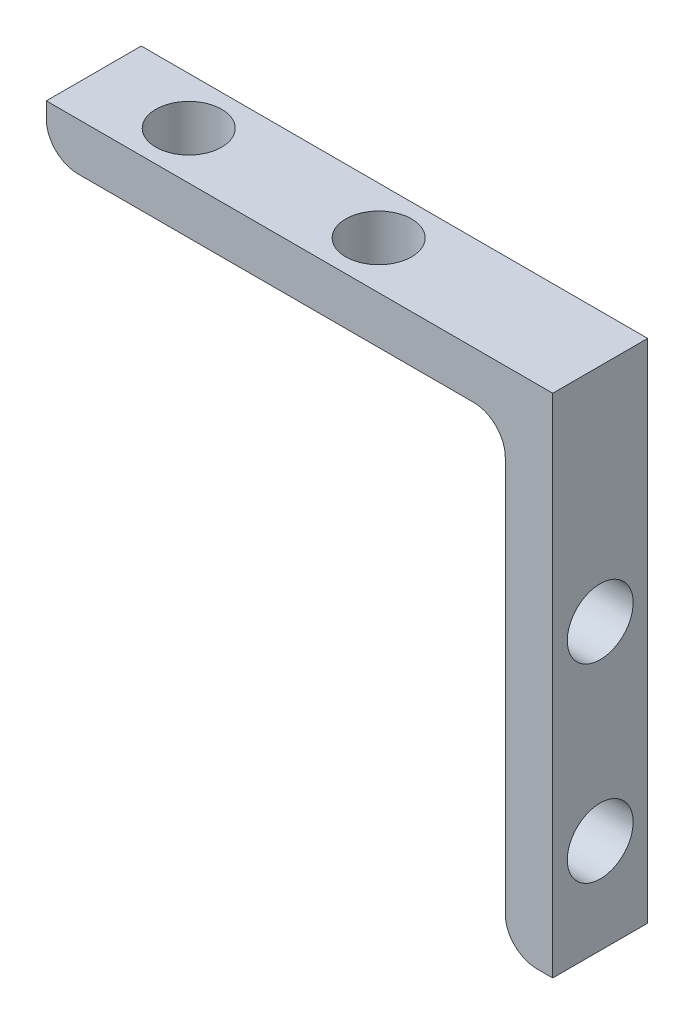
SolidWorks part; units mm, degrees
material "6061-T6 (SS)"
ref_plane "Front Plane" through (0, 0, 0) normal (0, 0, 1) x (1, 0, 0)
ref_plane "Top Plane" through (0, 0, 0) normal (0, 1, 0) x (1, 0, 0)
ref_plane "Right Plane" through (0, 0, 0) normal (1, 0, 0) x (0, 0, -1)
sketch "Sketch1" plane through (0, 0, 0) normal (0, 0, 1) x (1, 0, 0)
  line L28 (-50.8, 0) -> (0, 0)
  line L29 (0, 0) -> (0, -50.8)
  line L30 (0, -50.8) -> (-4.7625, -50.8)
  line L31 (-4.7625, -50.8) -> (-4.7625, -4.7625)
  line L32 (-4.7625, -4.7625) -> (-50.8, -4.7625)
  line L33 (-50.8, -4.7625) -> (-50.8, 0)
  dimension "D1" = 4.7625
  dimension "D2" = 50.8
extrude "Boss-Extrude1" add sketch "Sketch1" along normal blind 9.525
fillet "Fillet1" radius 3.175 3 edges at (-4.7625, -50.8, 4.7625) (-50.8, -4.7625, 4.7625) (-4.7625, -4.7625, 4.7625)
sketch "Sketch2" plane through (-4.7625, 0, 0) normal (-1, 0, 0) x (0, 0, 1)
  line L0 (4.7625, -50.8) -> (4.7625, -41.275) construction
  line L1 (9.525, -50.8) -> (0, -50.8) construction
  line L2 (4.7625, -41.275) -> (4.7625, -22.225) construction
  line L3 (4.7625, -22.225) -> (4.7625, -7.9375) construction
  line L4 (9.525, -7.9375) -> (0, -7.9375) construction
  line L5 (0, -47.625) -> (9.525, -47.625) construction
  circle A0 centre (4.7625, -41.275) radius 3.302
  circle A1 centre (4.7625, -22.225) radius 3.302
  point P10 (4.7625, -15.9837)
  point P11 (4.7625, -23.4019)
  dimension "D1" = 6.604
  dimension "D2" = 19.05
  dimension "D3" = 6.35
extrude "Cut-Extrude1" cut sketch "Sketch2" against normal through all
sketch "Sketch3" plane through (0, -4.7625, 0) normal (0, -1, 0) x (1, 0, 0)
  line L0 (-47.625, 4.7625) -> (-41.275, 4.7625) construction
  line L1 (-47.625, 9.525) -> (-47.625, 0) construction
  line L2 (-41.275, 4.7625) -> (-22.225, 4.7625) construction
  line L3 (-22.225, 4.7625) -> (-7.9375, 4.7625) construction
  line L4 (-7.9375, 0) -> (-7.9375, 9.525) construction
  circle A0 centre (-41.275, 4.7625) radius 3.302
  circle A1 centre (-22.225, 4.7625) radius 3.302
  dimension "D3" = 6.604
  dimension "D1" = 19.05
  dimension "D2" = 6.35
extrude "Cut-Extrude2" cut sketch "Sketch3" against normal through all
